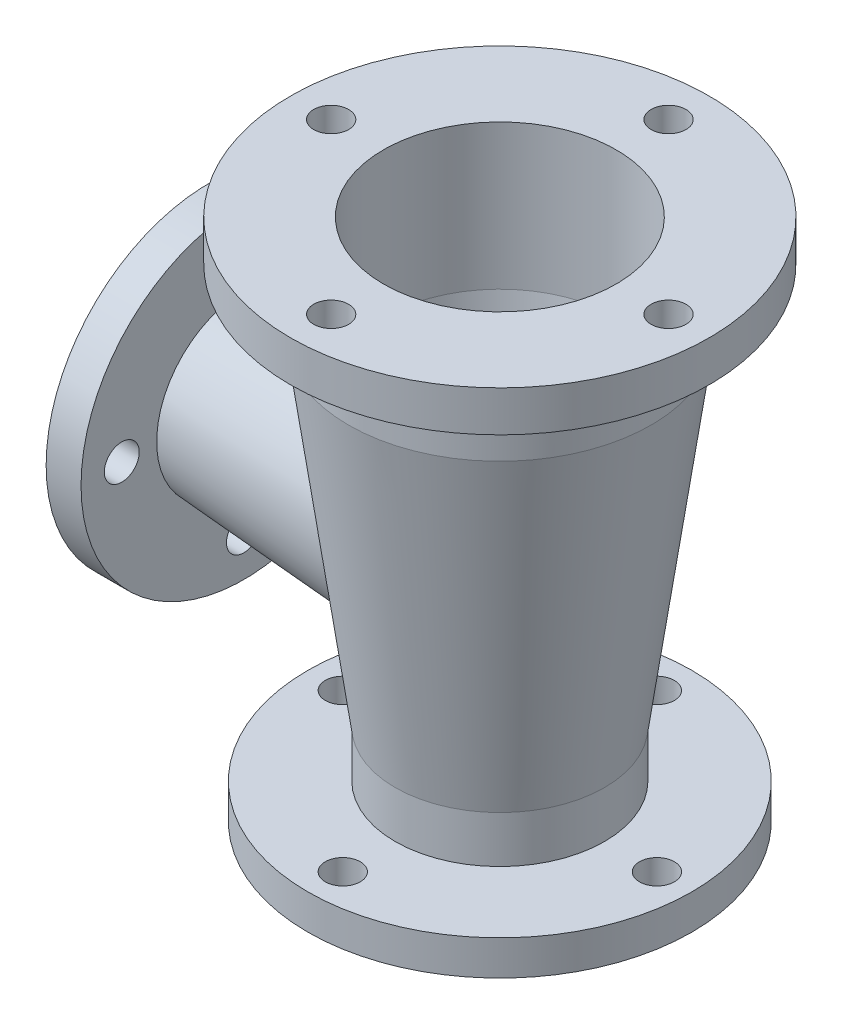
SolidWorks part; units mm, degrees
ref_plane "Front Plane" through (0, 0, 0) normal (0, 0, 1) x (1, 0, 0)
ref_plane "Top Plane" through (0, 0, 0) normal (0, 1, 0) x (1, 0, 0)
ref_plane "Right Plane" through (0, 0, 0) normal (1, 0, 0) x (0, 0, -1)
sketch "Sketch1" plane through (0, 0, 0) normal (0, 0, 1) x (1, 0, 0)
  line L0 (0, 125.2267) -> (0, -125.2267) construction
  line L1 (40, 125.2267) -> (72, 125.2267)
  line L2 (72, 125.2267) -> (72, 111.2267)
  line L3 (72, 111.2267) -> (52, 111.2267)
  line L4 (52, 111.2267) -> (52, 89.2267)
  line L5 (52, 89.2267) -> (36, -26.7059)
  line L9 (66, -42.7733) -> (36, -42.7733)
  line L12 (27.5957, -14.4568) -> (40, 75.422)
  line L13 (40, 75.422) -> (40, 125.2267)
  line L14 (22.6427, -18.7733) -> (20, -18.7733)
  line L15 (20, -18.7733) -> (20, -54.7733)
  line L16 (20, -54.7733) -> (66, -54.7733)
  line L17 (66, -54.7733) -> (66, -42.7733)
  line L18 (36, -26.7059) -> (36, -42.7733)
  arc A0 (27.5957, -14.4568) -> (22.6427, -18.7733) centre (22.6427, -13.7733) cw
  point P2 (20, -36.7733)
  point P13 (27, -18.7733)
  point P43 (27, -18.7733)
  dimension "D9" = 132
  dimension "D12" = 5
  dimension "D1" = 14
  dimension "D2" = 36
  dimension "D3" = 12
  dimension "D4" = 40
  dimension "D5" = 40
  dimension "D6" = 52
  dimension "D7" = 72
  dimension "D8" = 54
  dimension "D10" = 10
  dimension "D11" = 36
  dimension "D13" = 72
revolve "Revolve1" add sketch "Sketch1" angle 360 about L0
sketch "Sketch2" plane through (0, -42.7733, 0) normal (0, 1, 0) x (1, 0, 0)
  circle A0 centre (0, 0) radius 54 construction
  circle A1 centre (0, 54) radius 6
  circle A2 centre (54, 0) radius 6
  circle A3 centre (0, -54) radius 6
  circle A4 centre (-54, 0) radius 6
  point P14 (0, 0)
  dimension "D1" = 108
  dimension "D2" = 12
  dimension "D3" = 4
extrude "Cut-Extrude1" cut sketch "Sketch2" against normal blind 108 contours A1 | A4 | A2 | A3
sketch "Sketch3" plane through (0, 125.2267, 0) normal (0, 1, 0) x (1, 0, 0)
  circle A0 centre (0, 0) radius 58 construction
  circle A1 centre (0, 58) radius 6
  circle A2 centre (58, 0) radius 6
  circle A3 centre (0, -58) radius 6
  circle A4 centre (-58, 0) radius 6
  point P14 (0, 0)
  dimension "D1" = 116
  dimension "D2" = 12
  dimension "D3" = 4
extrude "Cut-Extrude2" cut sketch "Sketch3" against normal blind 108
sketch "Sketch4" plane through (0, 0, 0) normal (0, 0, 1) x (1, 0, 0)
  line L0 (0, 125.2267) -> (0, -54.7733) construction
  line L1 (6, 125.2267) -> (-6, 125.2267) construction
  line L2 (-66, -54.7733) -> (66, -54.7733) construction
  line L3 (-100, 29.2267) -> (83.6456, 29.2267) construction
  line L4 (64, 125.2267) -> (52, 125.2267) construction
  line L5 (-100, 29.2267) -> (-100, 85.2267)
  line L6 (-100, 85.2267) -> (-88, 85.2267)
  line L7 (-88, 85.2267) -> (-88, 59.2267)
  line L8 (-88, 59.2267) -> (0, 65.2267)
  line L9 (0, 65.2267) -> (0, 29.2267)
  line L10 (0, 29.2267) -> (-100, 29.2267)
  dimension "D1" = 96
  dimension "D2" = 56
  dimension "D3" = 100
  dimension "D4" = 12
  dimension "D5" = 30
  dimension "D6" = 36
revolve "Revolve2" add sketch "Sketch4" angle 360 about L10
sketch "Sketch5" plane through (0, 0, 0) normal (0, 0, 1) x (1, 0, 0)
  line L0 (0, 125.2267) -> (0, 111.2267) construction
  line L1 (6, 125.2267) -> (-6, 125.2267) construction
  line L3 (0, 111.2267) -> (40, 111.2267)
  line L10 (0, 111.2267) -> (0, -14.4568)
  line L13 (0, -14.4568) -> (27.5, -14.4568)
  line L14 (27.5957, -14.4568) -> (-27.5957, -14.4568) construction
  line L15 (27.5, -14.4568) -> (40, 75.422)
  line L16 (40, 75.422) -> (-40, 75.422) construction
  line L17 (40, 75.422) -> (40, 111.2267)
  dimension "D1" = 40
  dimension "D2" = 27.5
revolve "Cut-Revolve2" cut sketch "Sketch5" angle 360 about L0
sketch "Sketch6" plane through (0, 0, 0) normal (0, 0, 1) x (1, 0, 0)
  line L0 (0, 125.2267) -> (0, -54.7733) construction
  line L1 (72, 125.2267) -> (-72, 125.2267) construction
  line L2 (-66, -54.7733) -> (66, -54.7733) construction
  line L3 (-100, 29.2267) -> (-100, 49.2267)
  line L4 (-100, 85.2267) -> (-100, -26.7733) construction
  line L5 (-100, 49.2267) -> (0, 55.2267)
  line L6 (0, 55.2267) -> (0, 29.2267)
  line L7 (0, 29.2267) -> (-100, 29.2267)
  dimension "D1" = 20
  dimension "D2" = 26
revolve "Cut-Revolve3" cut sketch "Sketch6" angle 360 about L7
sketch "Sketch7" plane through (-100, 0, 0) normal (-1, 0, 0) x (0, 0, 1)
  line L0 (0, 85.2267) -> (0, -26.7733) construction
  circle A0 centre (0, 29.2267) radius 56 construction
  circle A1 centre (0, 29.2267) radius 42 construction
  circle A2 centre (0, 71.2267) radius 6
  circle A3 centre (42, 29.2267) radius 6
  circle A4 centre (0, -12.7733) radius 6
  circle A5 centre (-42, 29.2267) radius 6
  point P18 (0, 29.2267)
  dimension "D1" = 84
  dimension "D2" = 12
  dimension "D3" = 4
extrude "Cut-Extrude3" cut sketch "Sketch7" against normal blind 25
